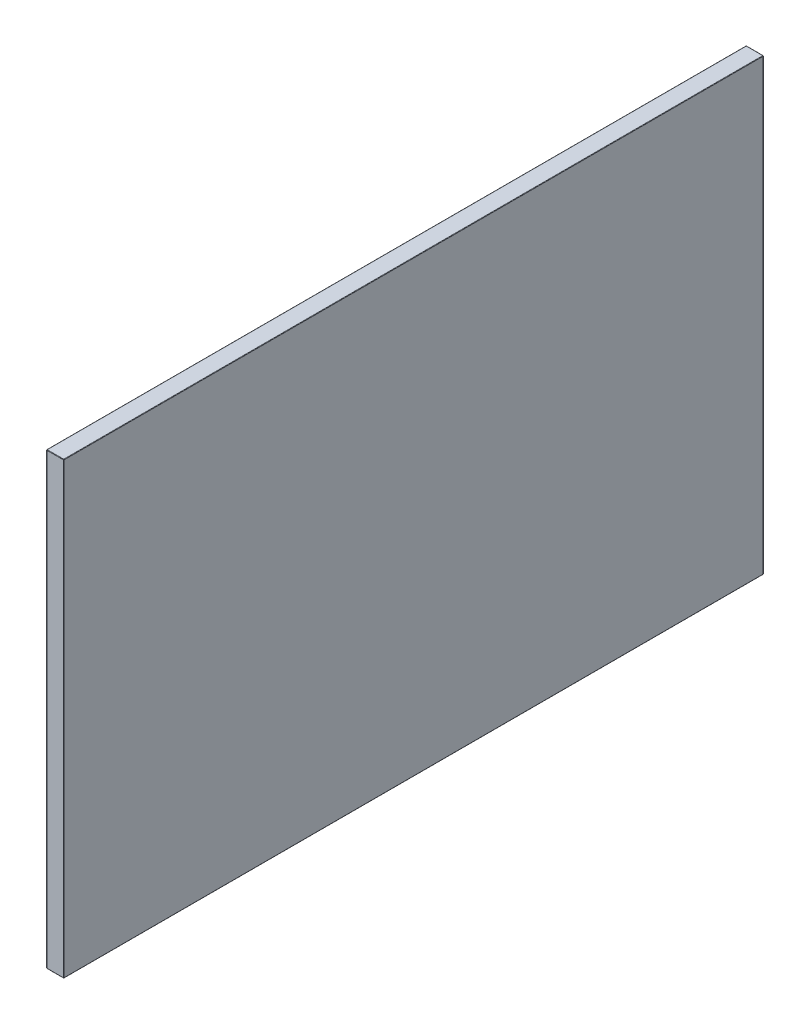
SolidWorks part; units mm, degrees
ref_plane "Front Plane" through (0, 0, 0) normal (0, 0, 1) x (1, 0, 0)
ref_plane "Top Plane" through (0, 0, 0) normal (0, 1, 0) x (1, 0, 0)
ref_plane "Right Plane" through (0, 0, 0) normal (1, 0, 0) x (0, 0, -1)
sketch "Sketch1" plane through (0, 0, 0) normal (1, 0, 0) x (0, 0, -1)
  line L1 (-405, 260) -> (405, 260)
  line L2 (-405, 260) -> (-405, -260)
  line L3 (-405, -260) -> (405, -260)
  line L4 (405, 260) -> (405, -260)
  line L5 (-405, 260) -> (405, -260) construction
  line L6 (-405, -260) -> (405, 260) construction
  point P0 (0, 0)
  dimension "D1" = 810
  dimension "D2" = 520
extrude "Boss-Extrude1" add sketch "Sketch1" along normal blind 20 contours L2 L3 L4 L1
fillet "Fillet1" radius 0.5 12 edges at (20, 0, -405) (0, 0, -405) (20, -260, 0) (10, -260, -405) (0, -260, 0) (20, 0, 405) (10, -260, 405) (0, 0, 405) (10, 260, -405) (20, 260, 0) (10, 260, 405) (0, 260, 0)
